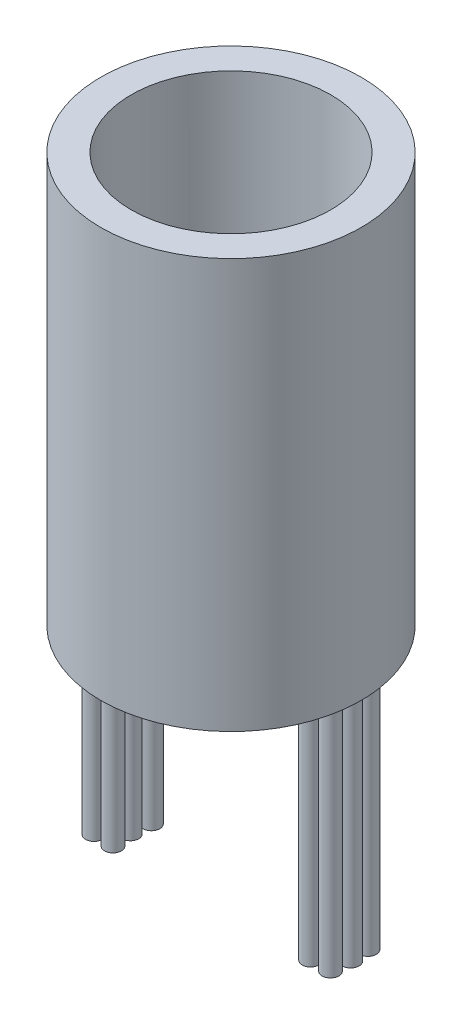
SolidWorks part; units mm, degrees
ref_plane "Front Plane" through (0, 0, 0) normal (0, 0, 1) x (1, 0, 0)
ref_plane "Top Plane" through (0, 0, 0) normal (0, 1, 0) x (1, 0, 0)
ref_plane "Right Plane" through (0, 0, 0) normal (1, 0, 0) x (0, 0, -1)
sketch "Sketch1" plane through (0, 0, 0) normal (0, 1, 0) x (1, 0, 0)
  circle A0 centre (0, 0) radius 6.2
  dimension "D1" = 12.4
extrude "Boss-Extrude1" add sketch "Sketch1" along normal blind 19.5
sketch "Sketch2" plane through (0, 19.5, 0) normal (0, 1, 0) x (1, 0, 0)
  circle A0 centre (0, 0) radius 2
  dimension "D1" = 4
extrude "Boss-Extrude2" add sketch "Sketch2" along normal blind 2.8
sketch "Sketch3" plane through (0, 22.3, 0) normal (0, 1, 0) x (1, 0, 0)
  circle A0 centre (-0.4115, -0.2373) radius 0.4
  circle A1 centre (-0.0913, 1.3462) radius 0.4
  circle A2 centre (0.7061, 1.1465) radius 0.4
  circle A3 centre (1.2337, 0.5162) radius 0.4
  circle A4 centre (1.2901, -0.3038) radius 0.4
  circle A5 centre (0.8538, -1.0004) radius 0.4
  circle A6 centre (0.0913, -1.3075) radius 0.4
  circle A7 centre (-0.7061, -1.1078) radius 0.4
  circle A8 centre (-1.2337, -0.4775) radius 0.4
  circle A9 centre (-1.2901, 0.3426) radius 0.4
  circle A10 centre (-0.8538, 1.0392) radius 0.4
  circle A11 centre (0, 0.5162) radius 0.4
  circle A12 centre (0.4417, -0.2373) radius 0.4
  point P25 (0, 0.0194)
  dimension "D1" = 0.8
  dimension "D3" = 10
extrude "Boss-Extrude4" add sketch "Sketch3" along normal blind 3.5
sketch "Sketch4" plane through (0, 19.5, 0) normal (0, 1, 0) x (1, 0, 0)
  circle A0 centre (0, 0) radius 4.75
  circle A1 centre (0, 0) radius 2 construction
  circle A2 centre (0, 0) radius 2
  dimension "D1" = 9.5
extrude "Cut-Extrude1" cut sketch "Sketch4" against normal blind 0.2
sketch "Sketch5" plane through (0, 0, 0) normal (0, -1, 0) x (1, 0, 0)
  line L0 (-1.52, 0) -> (1.4539, 0) construction
  line L1 (0, 1.5944) -> (0, -1.4457) construction
  circle A0 centre (-5.7001, 0) radius 0.4
  circle A1 centre (-5.6299, 0.8917) radius 0.4
  circle A2 centre (-4.7914, 0) radius 0.4
  circle A3 centre (-4.7034, 0.9142) radius 0.4
  circle A4 centre (-4.7034, -0.9142) radius 0.4
  circle A5 centre (-5.6299, -0.8917) radius 0.4
  circle A6 centre (5.6299, -0.8917) radius 0.4
  circle A7 centre (4.7034, -0.9142) radius 0.4
  circle A8 centre (4.7034, 0.9142) radius 0.4
  circle A9 centre (4.7914, 0) radius 0.4
  circle A10 centre (5.6299, 0.8917) radius 0.4
  circle A11 centre (5.7001, 0) radius 0.4
  point P6 (0, 0)
  point P12 (0, 0)
  dimension "D1" = 0.8
  dimension "D2" = 2
  dimension "D3" = 2
extrude "Boss-Extrude5" add sketch "Sketch5" along normal blind 11
sketch "Sketch6" plane through (0, 19.3, 0) normal (0, 1, 0) x (1, 0, 0)
  circle A1 centre (0, 0) radius 4.75
  circle A2 centre (0, 0) radius 4.75
  dimension "D1" = 0
extrude "Cut-Extrude3" cut sketch "Sketch6" against normal up to surface (19.3 mm away) and the other way through all up to face at (5.7001, 0, 0.4)
